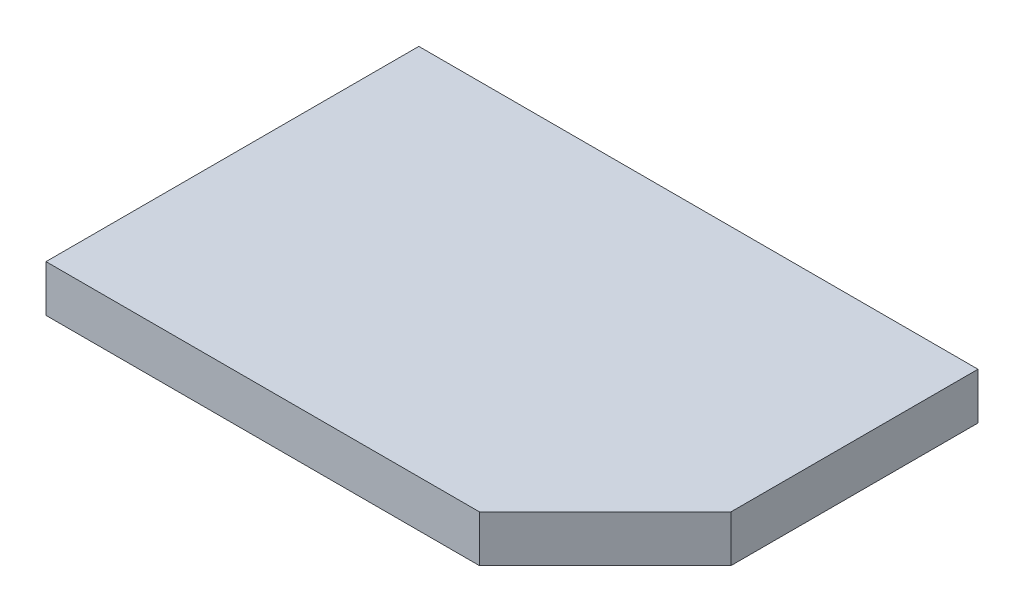
SolidWorks part; units mm, degrees
ref_plane "Plano frontal" through (0, 0, 0) normal (0, 0, 1) x (1, 0, 0)
ref_plane "Plano superior" through (0, 0, 0) normal (0, 1, 0) x (1, 0, 0)
ref_plane "Plano direito" through (0, 0, 0) normal (1, 0, 0) x (0, 0, -1)
sketch "Esboço1" plane through (0, 0, 0) normal (0, 1, 0) x (1, 0, 0)
  line L0 (0.6, 0.4) -> (-0.6, -0.4) construction
  line L1 (-0.6, 0.4) -> (0.6, 0.4)
  line L2 (-0.6, 0.4) -> (-0.6, -0.4)
  line L3 (-0.6, -0.4) -> (0.6, -0.4)
  line L4 (0.6, 0.4) -> (0.6, -0.4)
  dimension "D1" = 1.2
  dimension "D2" = 0.8
extrude "Extrusão1" add sketch "Esboço1" along normal blind 0.1
chamfer "Chanfro1" distance 0.27 angle 45 1 edges at (0.6, 0.05, 0.4)
